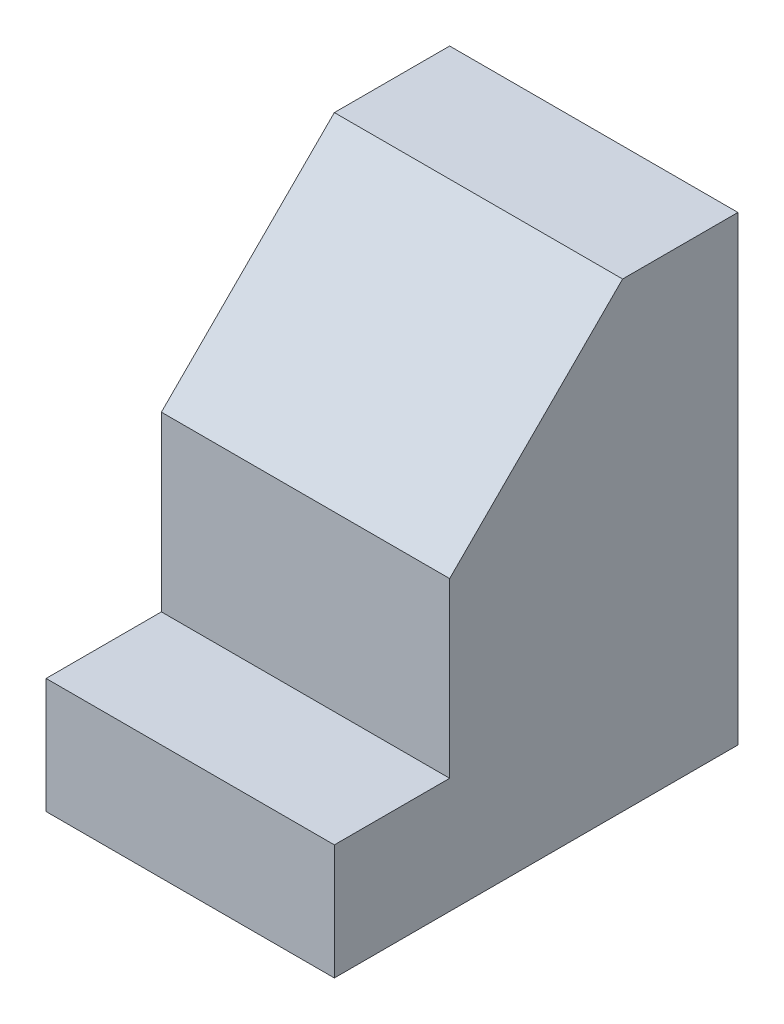
SolidWorks part; units mm, degrees
ref_plane "Ön Düzlem" through (0, 0, 0) normal (0, 0, 1) x (1, 0, 0)
ref_plane "Üst Düzlem" through (0, 0, 0) normal (0, 1, 0) x (1, 0, 0)
ref_plane "Sağ Düzlem" through (0, 0, 0) normal (1, 0, 0) x (0, 0, -1)
sketch "Sketch1" plane through (0, 0, 0) normal (0, 1, 0) x (1, 0, 0)
  line L0 (0, 0) -> (0, 35000)
  line L1 (0, 35000) -> (25000, 35000)
  line L2 (25000, 35000) -> (25000, 0)
  line L3 (0, 0) -> (25000, 0)
extrude "Boss-Extrude1" add sketch "Sketch1" along normal blind 10000 contours L3 L2 L1 L0
sketch "Sketch2" plane through (0, 0, 0) normal (0, 1, 0) x (1, 0, 0)
  line L0 (0, 35000) -> (0, 10000)
  line L1 (0, 0) -> (0, 35000) construction
  line L2 (0, 10000) -> (25000, 10000)
  line L3 (25000, 35000) -> (25000, 0) construction
  line L4 (25000, 10000) -> (25000, 35000)
  line L5 (25000, 35000) -> (0, 35000)
extrude "Boss-Extrude2" add sketch "Sketch2" along normal blind 25000
sketch "Sketch3" plane through (0, 0, 0) normal (0, 1, 0) x (1, 0, 0)
  line L0 (0, 35000) -> (0, 25000)
  line L1 (0, 35000) -> (0, 10000) construction
  line L2 (0, 35000) -> (25000, 35000)
  line L3 (25000, 35000) -> (25000, 25000)
  line L4 (25000, 10000) -> (25000, 35000) construction
  line L5 (25000, 25000) -> (0, 25000)
extrude "Boss-Extrude3" add sketch "Sketch3" along normal blind 40000
sketch "Sketch4" plane through (0, 0, 0) normal (1, 0, 0) x (0, 0, -1)
  line L0 (10000, 25000) -> (25000, 40000)
  line L1 (25000, 40000) -> (25000, 25000)
  line L2 (25000, 25000) -> (10000, 25000)
extrude "Boss-Extrude4" add sketch "Sketch4" along normal blind 25000
